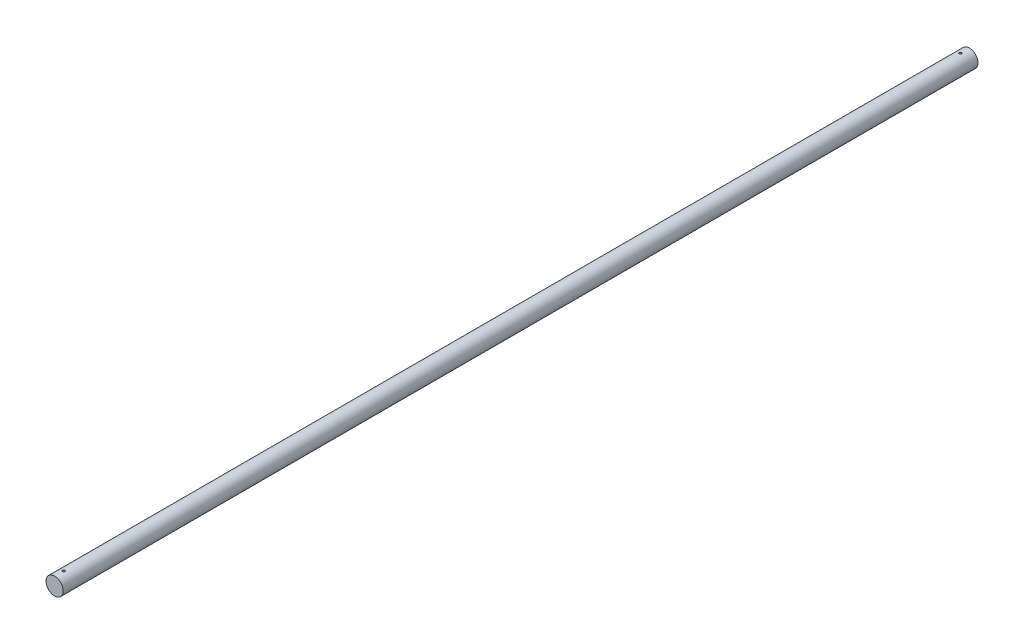
SolidWorks part; units mm, degrees
ref_plane "Front Plane" through (0, 0, 0) normal (0, 0, 1) x (1, 0, 0)
ref_plane "Top Plane" through (0, 0, 0) normal (0, 1, 0) x (1, 0, 0)
ref_plane "Right Plane" through (0, 0, 0) normal (1, 0, 0) x (0, 0, -1)
sketch "Sketch1" plane through (0, 0, 0) normal (0, 0, 1) x (1, 0, 0)
  circle A0 centre (0, 0) radius 5.5562
  dimension "D1" = 11.1125
extrude "Boss-Extrude1" add sketch "Sketch1" along normal mid plane 589.28
sketch "Sketch2" plane through (0, 0, 294.64) normal (0, 0, 1) x (1, 0, 0)
  line L0 (0, 5.5562) -> (0, -5.5562) construction
  circle A0 centre (0, 0) radius 5.5562 construction
sketch "Sketch3" plane through (0, 0, -294.64) normal (0, 0, -1) x (-1, 0, 0)
  line L0 (0, 5.5562) -> (0, -5.5562) construction
  circle A0 centre (0, 0) radius 5.5562 construction
ref_plane "Plane1" through (0, 0, 0) normal (-1, 0, 0) x (0, -1, 0)
sketch "Sketch4" plane through (0, 0, 0) normal (0, 1, 0) x (1, 0, 0)
  line L0 (0, -294.64) -> (0, 294.64) construction
  line L1 (0, 6.1119) -> (0, -6.1119) construction
  line L2 (-5.5562, -294.64) -> (5.5562, -294.64) construction
  line L3 (-16.5504, 0) -> (21.859, 0) construction
  circle A0 centre (0, -288.798) radius 0.762
  circle A1 centre (0, 288.798) radius 0.762
  dimension "D1" = 1.524
  dimension "D2" = 5.842
extrude "Cut-Extrude1" cut sketch "Sketch4" against normal mid plane 13.716
